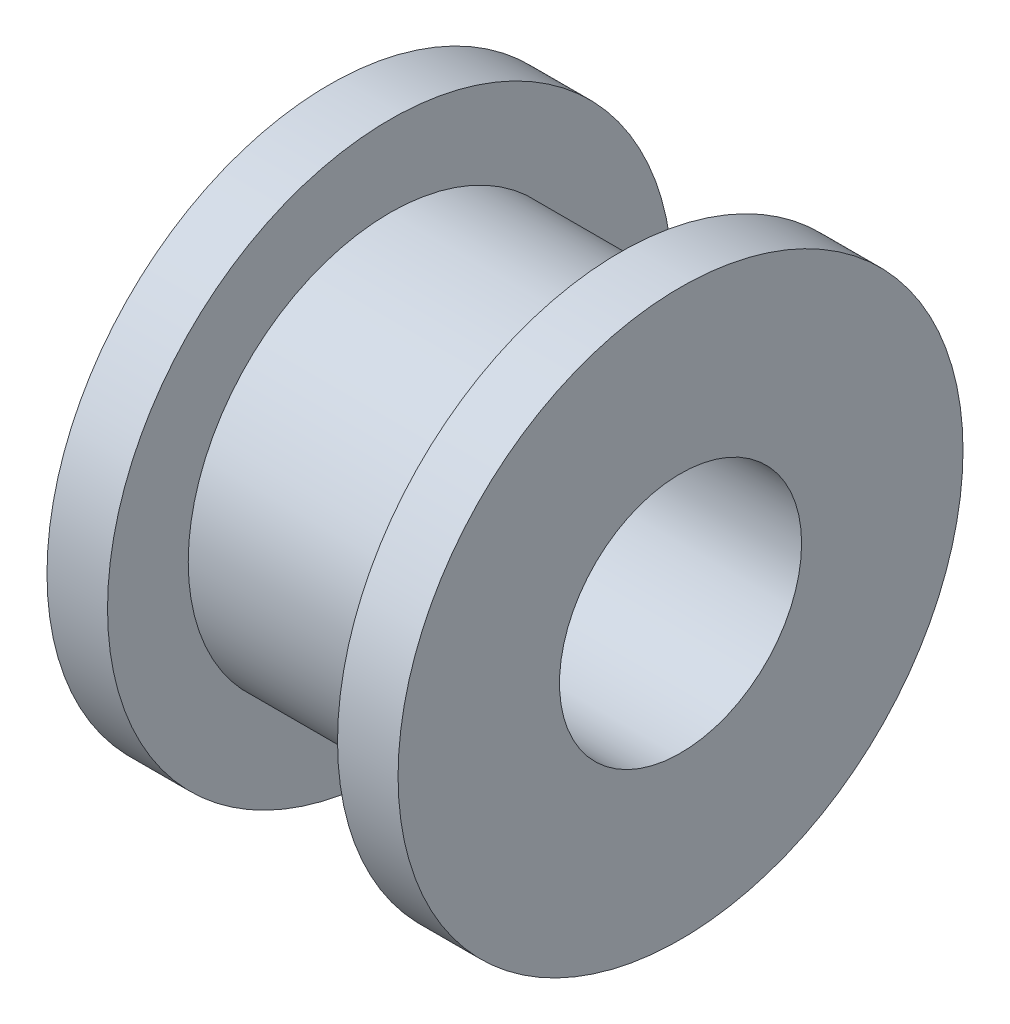
SolidWorks part; units mm, degrees
ref_plane "前视" through (0, 0, 0) normal (0, 0, 1) x (1, 0, 0)
ref_plane "上视" through (0, 0, 0) normal (0, 1, 0) x (1, 0, 0)
ref_plane "右视" through (0, 0, 0) normal (1, 0, 0) x (0, 0, -1)
sketch "草图1" plane through (0, 0, 0) normal (1, 0, 0) x (0, 0, -1)
  circle A0 centre (0, 0) radius 5
  dimension "D1" = 10
extrude "凸台-拉伸1" add sketch "草图1" along normal blind 8.7
sketch "草图2" plane through (8.7, 0, 0) normal (1, 0, 0) x (0, 0, -1)
  circle A0 centre (0, 0) radius 7
  dimension "D1" = 14
extrude "凸台-拉伸2" add sketch "草图2" against normal blind 1.5
sketch "草图3" plane through (0, 0, 0) normal (-1, 0, 0) x (0, 0, 1)
  circle A0 centre (0, 0) radius 7
  dimension "D1" = 14
extrude "凸台-拉伸3" add sketch "草图3" against normal blind 1.5
sketch "草图4" plane through (8.7, 0, 0) normal (1, 0, 0) x (0, 0, -1)
  circle A0 centre (0, 0) radius 3
  dimension "D1" = 6
extrude "切除-拉伸1" cut sketch "草图4" against normal blind 10
